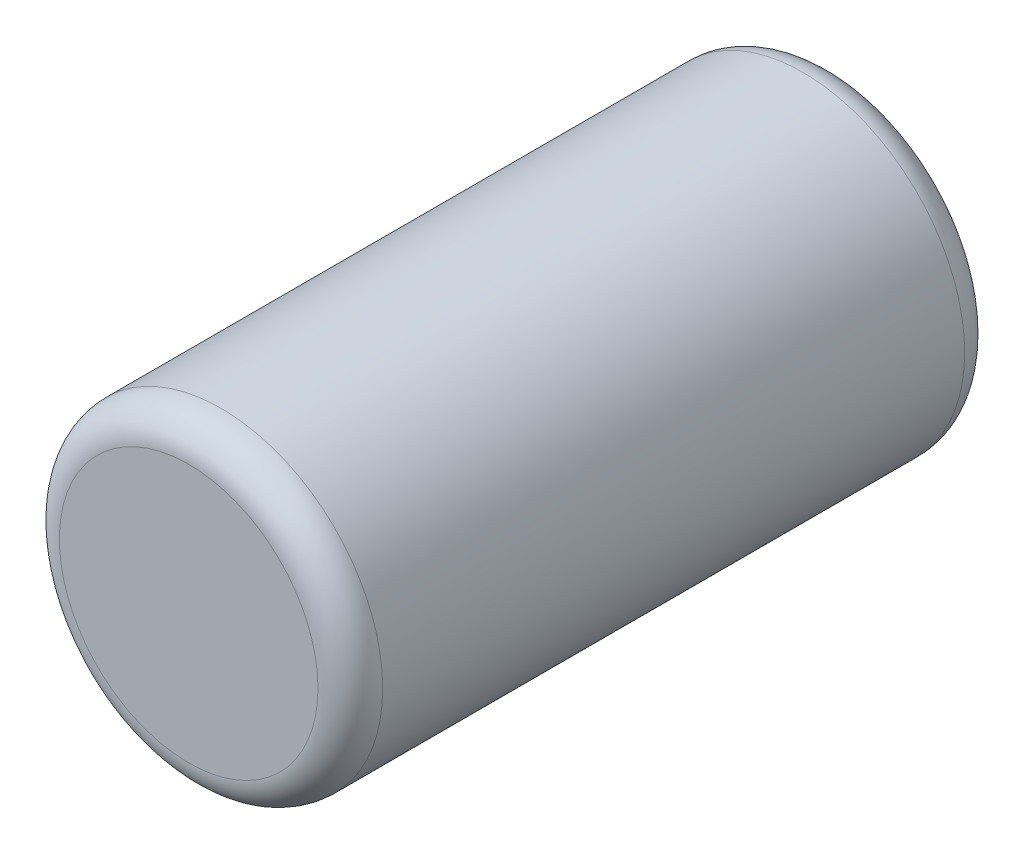
SolidWorks part; units mm, degrees
material "普通碳钢"
ref_plane "前视基准面" through (0, 0, 0) normal (0, 0, 1) x (1, 0, 0)
ref_plane "上视基准面" through (0, 0, 0) normal (0, 1, 0) x (1, 0, 0)
ref_plane "右视基准面" through (0, 0, 0) normal (1, 0, 0) x (0, 0, -1)
sketch "草图1" plane through (0, 0, 0) normal (0, 0, 1) x (1, 0, 0)
  circle A0 centre (0, 0) radius 1.5
  dimension "D1" = 3
extrude "拉伸1" add sketch "草图1" along direction (0, 0, 1) on the side of the normal mid plane 6
fillet "圆角1" radius 0.3 1 edges at (1.5, 0, 3)
fillet "圆角2" radius 0.3 1 edges at (1.5, 0, -3)
